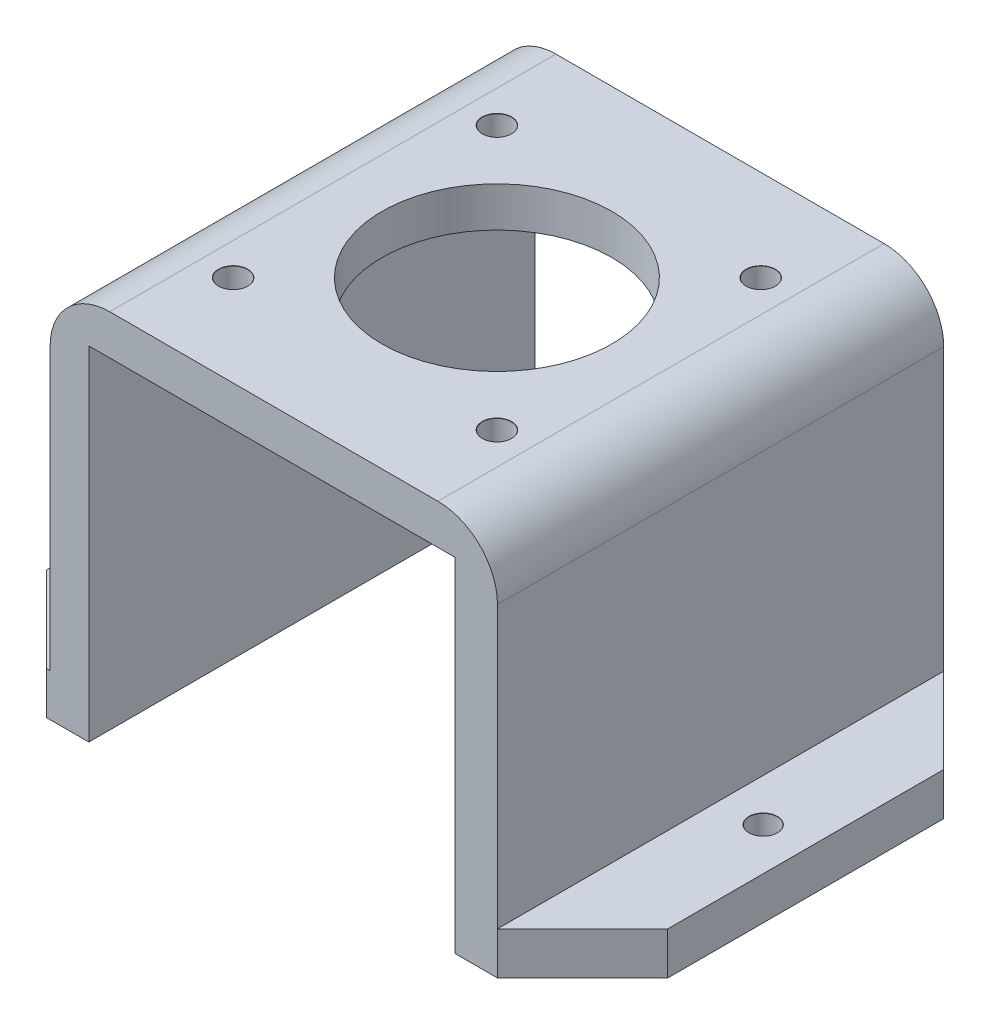
SolidWorks part; units mm, degrees
ref_plane "Front Plane" through (0, 0, 0) normal (0, 0, 1) x (1, 0, 0)
ref_plane "Top Plane" through (0, 0, 0) normal (0, 1, 0) x (1, 0, 0)
ref_plane "Right Plane" through (0, 0, 0) normal (1, 0, 0) x (0, 0, -1)
sketch "Sketch1" plane through (0, 0, 0) normal (0, 1, 0) x (1, 0, 0)
  line L0 (0, 52.418) -> (-43, 52.418)
  line L1 (0, 0) -> (15, 0)
  line L2 (0, 0) -> (0, 52.418)
  line L3 (0, 52.418) -> (15, 52.418)
  line L4 (15, 0) -> (15, 52.418)
  line L5 (-43, 52.418) -> (-43, 0)
  line L6 (-43, 0) -> (-58, 0)
  line L8 (-43, 52.418) -> (-58, 52.418)
  line L9 (-43, 52.418) -> (-43, 0)
  line L10 (-43, 0) -> (-58, 0)
  line L11 (-58, 52.418) -> (-58, 0)
extrude "Boss-Extrude1" add sketch "Sketch1" along normal blind 45 contours L1 L4 L3 L2 | L9 L8 L11 L10
sketch "Sketch2" plane through (0, 45, 0) normal (0, 1, 0) x (1, 0, 0)
  line L0 (-43, 52.418) -> (-47.5484, 52.418)
  line L1 (-43, 52.418) -> (-58, 52.418) construction
  line L2 (0, 52.418) -> (5, 52.418)
  line L3 (0, 52.418) -> (15, 52.418) construction
  line L5 (-47.5484, 52.418) -> (-58, 52.418)
  line L6 (-47.5484, 52.418) -> (-47.5484, 0)
  line L7 (-47.5484, 0) -> (-58, 0)
  line L8 (-58, 52.418) -> (-58, 0)
  line L9 (5, 52.418) -> (15, 52.418)
  line L10 (5, 52.418) -> (5, 0)
  line L11 (5, 0) -> (15, 0)
  line L12 (15, 52.418) -> (15, 0)
  line M1 (-58, 0) -> (-43, 0)
  line M3 (-43, 52.418) -> (-58, 52.418)
  line M4 (-58, 52.418) -> (-58, 0)
extrude "Cut-Extrude1" cut sketch "Sketch2" against normal blind 40 contours L6 M3 M4 M1 | L12 L9 L10 L11
sketch "Sketch3" plane through (0, 0, 0) normal (-1, 0, 0) x (0, 0, 1)
  line L0 (-52.418, 45) -> (-52.418, 40.3)
  line L2 (-52.418, 45) -> (-52.418, 0) construction
  line L4 (-52.418, 40.3) -> (0, 40.3)
  line L5 (-52.418, 40.3) -> (-52.418, 45)
  line L6 (-52.418, 45) -> (0, 45)
  line L7 (0, 40.3) -> (0, 45)
  line M2 (0, 0) -> (0, 45)
  line M3 (0, 45) -> (-52.418, 45)
  line M4 (-52.418, 45) -> (-52.418, 0)
extrude "Boss-Extrude3" add sketch "Sketch3" along normal blind 44 contours L4 M4 M2 M3
sketch "Sketch4" plane through (0, 45, 0) normal (0, 1, 0) x (1, 0, 0)
  line L13 (-36.7682, 10.715) -> (-5.7802, 10.715)
  line L14 (-36.7682, 10.715) -> (-36.7682, 41.703)
  line L15 (-36.7682, 41.703) -> (-5.7802, 41.703)
  line L16 (-5.7802, 10.715) -> (-5.7802, 41.703)
  line L17 (-36.7682, 10.715) -> (-5.7802, 41.703) construction
  line L18 (-36.7682, 41.703) -> (-5.7802, 10.715) construction
  circle A0 centre (-21.2742, 26.209) radius 13.5
  point P12 (-21.2742, 26.209)
  point P17 (-21.2742, 26.209)
hole_wizard "M3 Clearance Hole1" positions "Sketch6" profile "Sketch7" hole size "M3" standard "ANSI Metric" end condition through all
sketch "Sketch6" plane through (0, 45, 0) normal (0, 1, 0) x (1, 0, 0)
  point P0 (-36.7682, 41.703)
  point P3 (-5.7802, 41.703)
  point P6 (-5.7802, 10.715)
  point P9 (-36.7682, 10.715)
sketch "Sketch7" plane through (-36.7682, 45, -41.703) normal (1, 0, 0) x (0, 0, 1)
  line L0 (0, 0) -> (0, 45)
  line L1 (0, 45) -> (1.7, 45)
  line L2 (1.7, 45) -> (1.7, 0.025)
  line L3 (1.7, 0.025) -> (1.725, 0)
  line L5 (1.725, 0) -> (0, 0)
  line L6 (-1.7, 0.025) -> (-1.725, 0) construction
  line L11 (0, -6.35) -> (0, 107.95) construction
  dimension "Thru Hole Dia." = 3.4
  dimension "Thru Hole Depth" = 45
  dimension "Near C'Sink Dia." = 3.45
  dimension "Near C'Sink Angle" = 90
extrude "Cut-Extrude2" cut sketch "Sketch4" against normal blind 44 contours A0
sketch "Sketch10" plane through (0, 5, 0) normal (0, 1, 0) x (1, 0, 0)
  line L0 (-52.7742, 52.418) -> (-52.7742, 26.209)
  line L1 (-47.5484, 52.418) -> (-58, 52.418) construction
  line L2 (10, 52.418) -> (10, 26.209)
  line L3 (5, 52.418) -> (15, 52.418) construction
hole_wizard "Tap Drill for M4x0.7 Tap1" positions "Sketch11" profile "Sketch12" hole size "M4x0.7" standard "ANSI Metric" end condition through all
sketch "Sketch11" plane through (0, 5, 0) normal (0, 1, 0) x (1, 0, 0)
  point P0 (-52.7742, 26.209)
  point P3 (10, 26.209)
sketch "Sketch12" plane through (-52.7742, 5, -26.209) normal (1, 0, 0) x (0, 0, 1)
  line L0 (0, 0) -> (0, 5)
  line L1 (0, 5) -> (1.65, 5)
  line L2 (1.65, 5) -> (1.65, 0.025)
  line L3 (1.65, 0.025) -> (1.675, 0)
  line L5 (1.675, 0) -> (0, 0)
  line L6 (-1.65, 0.025) -> (-1.675, 0) construction
  line L11 (0, -6.35) -> (0, 107.95) construction
  dimension "Thru Hole Dia." = 3.3
  dimension "Thru Hole Depth" = 5
  dimension "Near C'Sink Dia." = 3.35
  dimension "Near C'Sink Angle" = 90
chamfer "Chamfer1" distance 10 angle 45 4 edges at (-58, 2.5, -52.418) (15, 2.5, -52.418) (15, 2.5, 0) (-58, 2.5, 0)
fillet "Fillet1" radius 7 2 edges at (5, 45, -26.209) (-47.5484, 45, -26.209)
sketch "Sketch13" plane through (0, 0, 0) normal (0, -1, 0) x (1, 0, 0)
  line L0 (10, -26.209) -> (10, -5)
  line L2 (-52.7742, -26.209) -> (-52.7742, -4.7742)
  line L3 (-52.7742, -4.7742) -> (-21.5, 26.5)
  line L4 (10, -5) -> (-21.5, 26.5)
  dimension "D1" = 135
